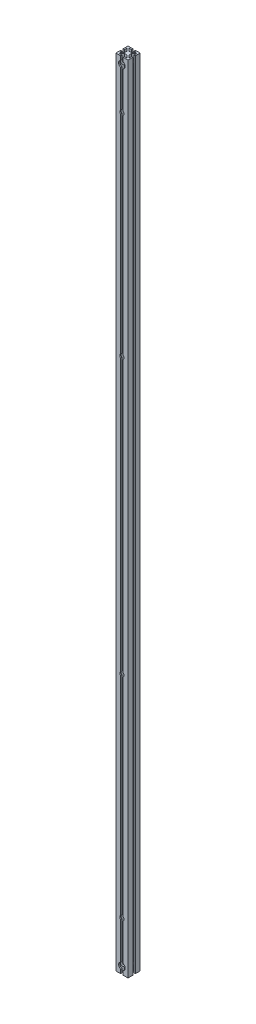
SolidWorks part; units mm, degrees
ref_plane "Front Plane" through (0, 0, 0) normal (0, 0, 1) x (1, 0, 0)
ref_plane "Top Plane" through (0, 0, 0) normal (0, 1, 0) x (1, 0, 0)
ref_plane "Right Plane" through (0, 0, 0) normal (1, 0, 0) x (0, 0, -1)
sketch "Sketch2" plane through (0.5947, 0, 0.5947) normal (0, 1, 0) x (1, 0, 0)
  line L0 (-0.5947, 0.5947) -> (-0.5947, 20.2394) construction
  line L1 (-0.5947, 0.5947) -> (-20.2394, 0.5947) construction
  line L2 (-0.5947, 0.5947) -> (-20.2394, 20.2394) construction
  line L3 (-19.6447, 19.6447) -> (-4.6587, 19.6447)
  line L4 (-4.6587, 19.6447) -> (-4.6587, 15.5807)
  line L5 (-4.6587, 15.5807) -> (-12.707, 15.5807)
  line L6 (-12.707, 15.5807) -> (-4.4774, 7.3511)
  line L7 (-4.4774, 7.3511) -> (3.288, 7.3511)
  line L8 (-19.6447, 19.6447) -> (-19.6447, 4.6587)
  line L9 (-19.6447, 4.6587) -> (-15.5807, 4.6587)
  line L10 (-15.5807, 4.6587) -> (-15.5807, 12.707)
  line L11 (-15.5807, 12.707) -> (-7.3511, 4.4774)
  line L12 (-7.3511, 4.4774) -> (-7.3511, -3.288)
  line L13 (-4.4774, -6.1617) -> (3.288, -6.1617)
  line L14 (-12.707, -14.3913) -> (-4.4774, -6.1617)
  line L15 (-4.6587, -14.3913) -> (-12.707, -14.3913)
  line L16 (-4.6587, -18.4553) -> (-4.6587, -14.3913)
  line L17 (-19.6447, -18.4553) -> (-4.6587, -18.4553)
  line L18 (-19.6447, -18.4553) -> (-19.6447, -3.4693)
  line L19 (-19.6447, -3.4693) -> (-15.5807, -3.4693)
  line L20 (-15.5807, -3.4693) -> (-15.5807, -11.5176)
  line L21 (-15.5807, -11.5176) -> (-7.3511, -3.288)
  line L22 (11.5176, 15.5807) -> (3.288, 7.3511)
  line L23 (3.4693, 15.5807) -> (11.5176, 15.5807)
  line L24 (3.4693, 19.6447) -> (3.4693, 15.5807)
  line L25 (18.4553, 19.6447) -> (3.4693, 19.6447)
  line L26 (18.4553, 19.6447) -> (18.4553, 4.6587)
  line L27 (18.4553, 4.6587) -> (14.3913, 4.6587)
  line L28 (14.3913, 4.6587) -> (14.3913, 12.707)
  line L29 (14.3913, 12.707) -> (6.1617, 4.4774)
  line L30 (6.1617, 4.4774) -> (6.1617, -3.288)
  line L31 (14.3913, -11.5176) -> (6.1617, -3.288)
  line L32 (14.3913, -3.4693) -> (14.3913, -11.5176)
  line L33 (18.4553, -3.4693) -> (14.3913, -3.4693)
  line L34 (18.4553, -18.4553) -> (18.4553, -3.4693)
  line L35 (18.4553, -18.4553) -> (3.4693, -18.4553)
  line L36 (3.4693, -18.4553) -> (3.4693, -14.3913)
  line L37 (3.4693, -14.3913) -> (11.5176, -14.3913)
  line L38 (11.5176, -14.3913) -> (3.288, -6.1617)
  point P26 (-7.3511, 0.5947)
  point P27 (-0.5947, 7.3511)
  point P44 (-0.5947, -6.1617)
  dimension "D1" = 38.1
  dimension "D2" = 8.128
  dimension "D3" = 13.5128
  dimension "D4" = 4.064
  dimension "D5" = 4.064
extrude "Boss-Extrude1" add sketch "Sketch2" along normal blind 2486.025
other "1515<1>"
sketch "Sketch3" plane through (0, 0, 19.05) normal (0, 0, 1) x (1, 0, 0)
  line L0 (4.064, 2486.025) -> (19.05, 2486.025) construction
  circle A0 centre (0, 2464.181) radius 10.287
  dimension "D2" = 20.574
  dimension "D1" = 21.844
extrude "Cut-Extrude1" cut sketch "Sketch3" against normal blind 16.51
mirror "Mirror1" about plane through (0, 0, 0) normal (0, 0, 1) of "Cut-Extrude1"
ref_plane "midplane" through (0, 1243.0125, 0) normal (0, 1, 0) x (-1, 0, 0)
mirror "Mirror2" about plane through (0, 1243.0125, 0) normal (0, 1, 0) of "Mirror1", "Cut-Extrude1"
sketch "Sketch4" plane through (0, 0, 19.05) normal (0, 0, 1) x (1, 0, 0)
  line L0 (4.064, 2486.025) -> (19.05, 2486.025) construction
  line L1 (4.064, 2486.025) -> (12.1123, 2486.025) construction
  line L2 (4.064, 0) -> (19.05, 0) construction
  circle A0 centre (0, 2333.625) radius 4.1656
  circle A1 centre (0, 1673.225) radius 4.1656
  circle A2 centre (0, 812.8) radius 4.1656
  circle A3 centre (0, 152.4) radius 4.1656
  point P10 (8.0882, 2486.025)
  dimension "D1" = 8.3312
  dimension "D2" = 152.4
  dimension "D3" = 812.8
  dimension "D4" = 152.4
  dimension "D5" = 812.8
extrude "Cut-Extrude2" cut sketch "Sketch4" against normal through all
sketch "Sketch5" plane through (0, 0, 19.05) normal (0, 0, 1) x (1, 0, 0)
  circle A0 centre (0, 2333.625) radius 6.7437
  circle A1 centre (0, 1673.225) radius 6.7437
  circle A2 centre (0, 812.8) radius 6.7437
  circle A3 centre (0, 152.4) radius 6.7437
  dimension "D1" = 13.4874
extrude "Cut-Extrude3" cut sketch "Sketch5" against normal blind 12.319
